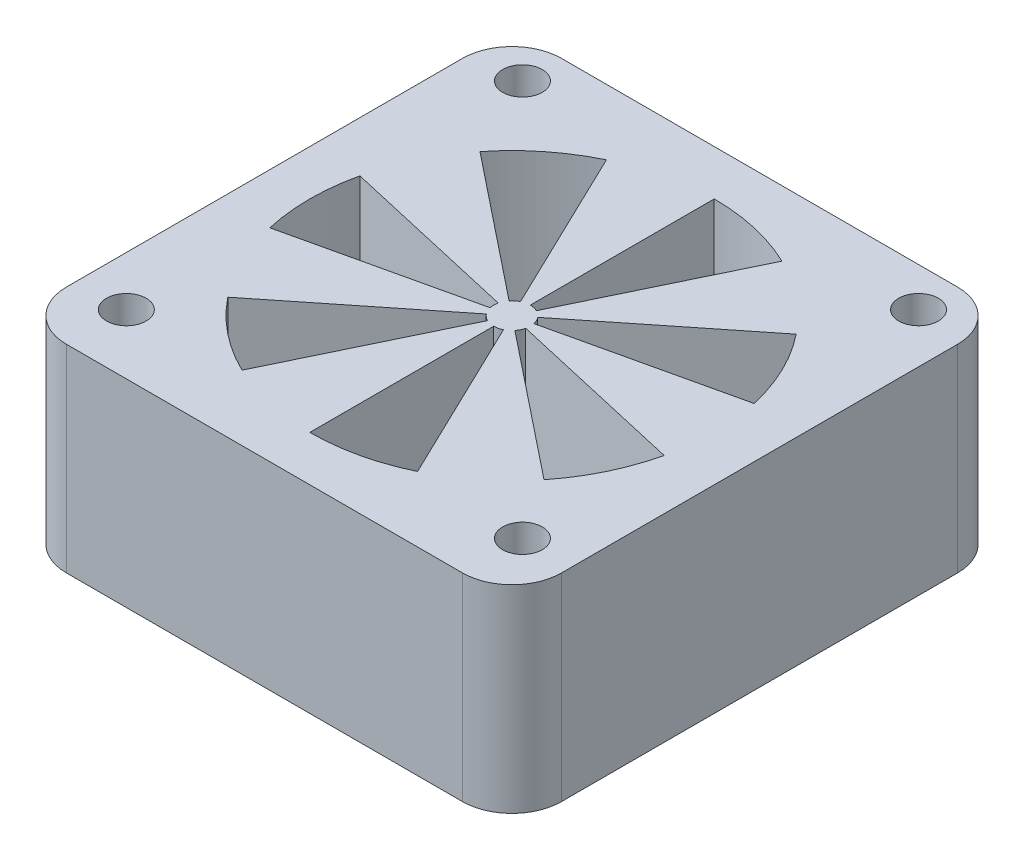
SolidWorks part; units mm, degrees
ref_plane "前视基准面" through (0, 0, 0) normal (0, 0, 1) x (1, 0, 0)
ref_plane "上视基准面" through (0, 0, 0) normal (0, 1, 0) x (1, 0, 0)
ref_plane "右视基准面" through (0, 0, 0) normal (1, 0, 0) x (0, 0, -1)
sketch "草图1" plane through (0, 0, 0) normal (0, 1, 0) x (1, 0, 0)
  line L1 (0, 0) -> (50, 0)
  line L2 (0, 0) -> (0, -50)
  line L3 (0, -50) -> (50, -50)
  line L4 (50, 0) -> (50, -50)
  dimension "D1" = 50
  dimension "D2" = 50
extrude "凸台-拉伸1" add sketch "草图1" along normal blind 20
sketch "草图2" plane through (0, 20, 0) normal (0, 1, 0) x (1, 0, 0)
  line L0 (5, -3.9455) -> (45, -3.9455) construction
  line L1 (45, -3.9455) -> (45, -43.9455) construction
  line L2 (45, -43.9455) -> (5, -43.9455) construction
  line L3 (5, -43.9455) -> (5, -3.9455) construction
  line L4 (25, -3.9455) -> (25, 0) construction
  line L5 (50, 0) -> (0, 0) construction
  circle A0 centre (5, -3.9455) radius 2
  circle A1 centre (45, -3.9455) radius 2
  circle A2 centre (5, -43.9455) radius 2
  circle A3 centre (45, -43.9455) radius 2
  dimension "D2" = 4
  dimension "D1" = 40
extrude "切除-拉伸1" cut sketch "草图2" against normal blind 20
sketch "草图3" plane through (0, 20, 0) normal (0, 1, 0) x (1, 0, 0)
  line L0 (25, -23.1552) -> (25, -4.5794)
  line L1 (25.8004, -23.3379) -> (33.8601, -6.6017)
  line L2 (26.4423, -23.8498) -> (40.9654, -12.268)
  line L3 (26.7985, -24.5895) -> (44.9086, -20.456)
  line L4 (26.7985, -25.4105) -> (44.9086, -29.544)
  line L5 (26.4423, -26.1502) -> (40.9654, -37.732)
  line L6 (25.8004, -26.6621) -> (33.8601, -43.3983)
  line L7 (25, -26.8448) -> (25, -45.4206)
  line L8 (24.1996, -26.6621) -> (16.1399, -43.3983)
  line L9 (23.5577, -26.1502) -> (9.0346, -37.732)
  line L10 (23.2015, -25.4105) -> (5.0914, -29.544)
  line L11 (23.2015, -24.5895) -> (5.0914, -20.456)
  line L12 (23.5577, -23.8498) -> (9.0346, -12.268)
  line L13 (24.1996, -23.3379) -> (16.1399, -6.6017)
  arc A0 (16.1399, -6.6017) -> (9.0346, -12.268) centre (25, -25) ccw
  arc A1 (5.0914, -20.456) -> (5.0914, -29.544) centre (25, -25) ccw
  arc A2 (9.0346, -37.732) -> (16.1399, -43.3983) centre (25, -25) ccw
  arc A3 (25, -45.4206) -> (33.8601, -43.3983) centre (25, -25) ccw
  arc A4 (40.9654, -37.732) -> (44.9086, -29.544) centre (25, -25) ccw
  arc A5 (44.9086, -20.456) -> (40.9654, -12.268) centre (25, -25) ccw
  arc A6 (33.8601, -6.6017) -> (25, -4.5794) centre (25, -25) ccw
  arc A7 (23.2015, -24.5895) -> (23.2015, -25.4105) centre (25, -25) ccw
  arc A8 (24.1996, -23.3379) -> (23.5577, -23.8498) centre (25, -25) ccw
  arc A9 (25.8004, -23.3379) -> (25, -23.1552) centre (25, -25) ccw
  arc A10 (26.7985, -24.5895) -> (26.4423, -23.8498) centre (25, -25) ccw
  arc A11 (26.4423, -26.1502) -> (26.7985, -25.4105) centre (25, -25) ccw
  arc A12 (25, -26.8448) -> (25.8004, -26.6621) centre (25, -25) ccw
  arc A13 (23.5577, -26.1502) -> (24.1996, -26.6621) centre (25, -25) ccw
  dimension "D1" = 14
extrude "切除-拉伸2" cut sketch "草图3" against normal blind 20
fillet "圆角1" radius 5 4 edges at (0, 10, 50) (50, 10, 50) (50, 10, 0) (0, 10, 0)
